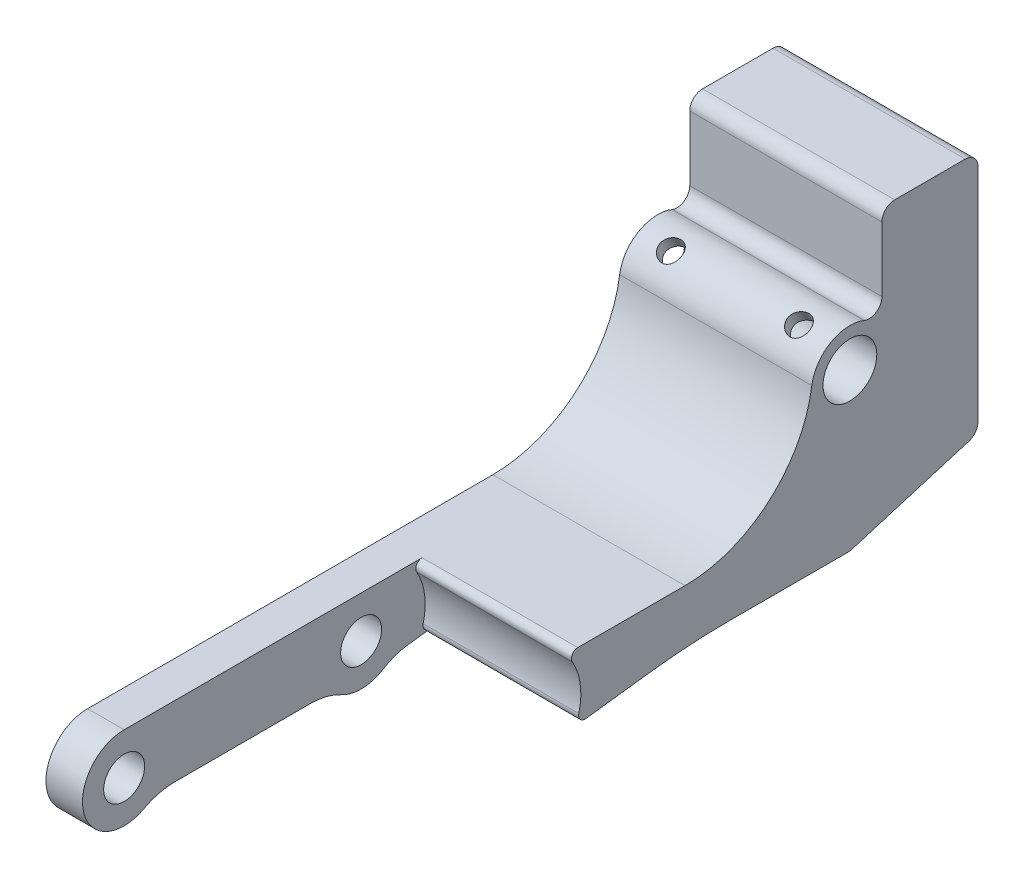
SolidWorks part; units mm, degrees
material "3DP"
ref_plane "正面" through (0, 0, 0) normal (0, 0, 1) x (1, 0, 0)
ref_plane "平面" through (0, 0, 0) normal (0, 1, 0) x (1, 0, 0)
ref_plane "右側面" through (0, 0, 0) normal (1, 0, 0) x (0, 0, -1)
sketch "ｽｹｯﾁ1" plane through (0, 0, 0) normal (1, 0, 0) x (0, 0, -1)
  line L0 (0, 0) -> (0, -38)
  line L1 (-20, -44) -> (-45, -44)
  line L2 (0, 0) -> (-15, 0)
  line L3 (-15, 0) -> (-15, -16.1834)
  line L4 (-22.3609, -13.984) -> (-73.3325, -35.8) construction
  line L5 (-109, -35.8) -> (-73.3325, -35.8)
  line L6 (-104.3096, -46.8) -> (-76.6904, -46.8)
  line L7 (-45, -44) -> (-67.3096, -46.8)
  line L8 (-73.3325, -35.8) -> (-74.5576, -36.3243) construction
  line L9 (-73.3325, -35.8) -> (-72, -35.8) construction
  line L10 (-20, -44) -> (0, -38)
  line L11 (0, -38) -> (0, -44) construction
  line L12 (0, -44) -> (-20, -44) construction
  line L13 (-72, -35.8) -> (-73.3325, -35.8)
  line L14 (-72, -35.8) -> (-45.7354, -35.8)
  arc A0 (-15, -16.1834) -> (-22.3609, -13.984) centre (-20, -19.5) ccw
  arc A1 (-72, -35.8) -> (-74.5576, -36.3243) centre (-72, -42.3) ccw construction
  arc A2 (-109, -35.8) -> (-104.3096, -46.8) centre (-109, -42.3) ccw
  arc A3 (-22.3609, -13.984) -> (-15, -16.1834) centre (-20, -19.5) ccw construction
  arc A4 (-67.3096, -46.8) -> (-72, -35.8) centre (-72, -42.3) ccw construction
  arc A5 (-74.5576, -36.3243) -> (-76.6904, -46.8) centre (-72, -42.3) ccw construction
  arc A6 (-76.6904, -46.8) -> (-67.3096, -46.8) centre (-72, -42.3) ccw
  arc A7 (-104.3096, -46.8) -> (-109, -35.8) centre (-109, -42.3) ccw construction
  circle A8 centre (-20, -19.5) radius 4.2
  circle A9 centre (-109, -42.3) radius 3.2
  circle A10 centre (-72, -42.3) radius 3.2
  arc A12 (-22.3609, -13.984) -> (-25.9389, -18.6462) centre (-20, -19.5) ccw
  arc A13 (-45.7354, -35.8) -> (-25.9389, -18.6462) centre (-45.7354, -15.8) ccw
  dimension "D2" = 13
  dimension "D3" = 37
  dimension "D7" = 72
  dimension "D8" = 20
  dimension "D9" = 19.5
  dimension "D11" = 6
  dimension "D12" = 8.4
  dimension "D13" = 6.4
  dimension "D16" = 20
  dimension "D1" = 15
  dimension "D4" = 45
  dimension "D5" = 44
  dimension "D6" = 42.3
  dimension "D10" = 11
  dimension "D14" = 6
  dimension "D15" = 20
extrude "ﾎﾞｽ - 押し出し1" add sketch "ｽｹｯﾁ1" along normal blind 30
sketch "ｽｹｯﾁ2" plane through (0, -35.8, 0) normal (0, 1, 0) x (1, 0, 0)
  line L0 (15, 0) -> (15, -115.5) construction
  line L1 (30, 0) -> (0, 0) construction
  line L2 (0, -115.5) -> (30, -115.5) construction
  circle A0 centre (15, -83.6) radius 5
  dimension "D1" = 83.6
  dimension "D2" = 10
extrude "ｶｯﾄ - 押し出し1" cut sketch "ｽｹｯﾁ2" against normal through all both and the other way through all
sketch "ｽｹｯﾁ4" plane through (30, 0, 0) normal (1, 0, 0) x (0, 0, -1)
  circle A0 centre (-72, -42.3) radius 8
  circle A1 centre (-109, -42.3) radius 8
  dimension "D1" = 16
extrude "ｶｯﾄ - 押し出し3" cut sketch "ｽｹｯﾁ4" against normal blind 24.3
sketch "ｽｹｯﾁ5" plane through (30, 0, 0) normal (1, 0, 0) x (0, 0, -1)
  line L0 (-109, -32.3) -> (-72, -32.3)
  line L1 (-109, -52.3) -> (-72, -52.3)
  arc A0 (-109, -32.3) -> (-109, -52.3) centre (-109, -42.3) ccw
  arc A1 (-72, -52.3) -> (-72, -32.3) centre (-72, -42.3) ccw
  point P1 (-72, -52.3)
  point P4 (-72, -42.3)
  dimension "D1" = 10
extrude "ｶｯﾄ - 押し出し4" cut sketch "ｽｹｯﾁ5" against normal up to surface (24.3 mm away) up to face at (5.7, -42.3, 68.8)
sketch "ｽｹｯﾁ6" plane through (30, 0, 0) normal (1, 0, 0) x (0, 0, -1)
  line L0 (-23, -14.3038) -> (-20, -19.5) construction
  line L1 (-20, -19.5) -> (-24.2, -19.5) construction
  circle A1 centre (-20, -19.5) radius 4.2 construction
  arc A2 (-15, -16.1834) -> (-25.9389, -18.6462) centre (-20, -19.5) ccw construction
  point P2 (-24.2, -19.5)
  point P3 (-20, -19.5)
  point P4 (-24.1847, -19.1415)
  point P6 (0, 0)
  point P10 (-20, -19.2988)
  point P11 (-23, -14.3038)
  dimension "D1" = 60
ref_plane "平面2" through (30, -14.3038, 23) normal (0, 0.866, 0.5) x (1, 0, 0)
sketch "ｽｹｯﾁ7" plane through (30, -14.3038, 23) normal (0, 0.866, 0.5) x (1, 0, 0)
  line L0 (-15, 5.9884) -> (-15, -4.7163) construction
  line L1 (0, 5.9884) -> (-30, 5.9884) construction
  line L2 (0, -4.7163) -> (-30, -4.7163) construction
  line L3 (-15, 0) -> (0, 0) construction
  line L4 (0, -4.7163) -> (0, 5.9884) construction
  circle A0 centre (-5, 0) radius 1.7
  circle A1 centre (-25, 0) radius 1.7
  point P8 (0, 0)
  point P14 (0, 0)
  dimension "D1" = 3.4
  dimension "D2" = 5
extrude "ｶｯﾄ - 押し出し5" cut sketch "ｽｹｯﾁ7" against normal up to surface (2.1594 mm away)
fillet "ﾌｨﾚｯﾄ1" radius 2 1 edges at (15, -16.1834, 15)
fillet "ﾌｨﾚｯﾄ2" radius 100 1 edges at (15, -44, 45)
fillet "ﾌｨﾚｯﾄ4" radius 2 4 edges at (15, -44, 20) (15, 0, 15) (15, 0, 0) (15, -38, 0)
fillet "ﾌｨﾚｯﾄ5" radius 1 2 edges at (17.85, -46.2349, 62.8067) (17.85, -35.8, 64.4007)
fillet "ﾌｨﾚｯﾄ6" radius 10 3 edges at (2.85, -46.8, 76.6904) (2.85, -46.8, 67.3096) (2.85, -46.8, 104.3096)
